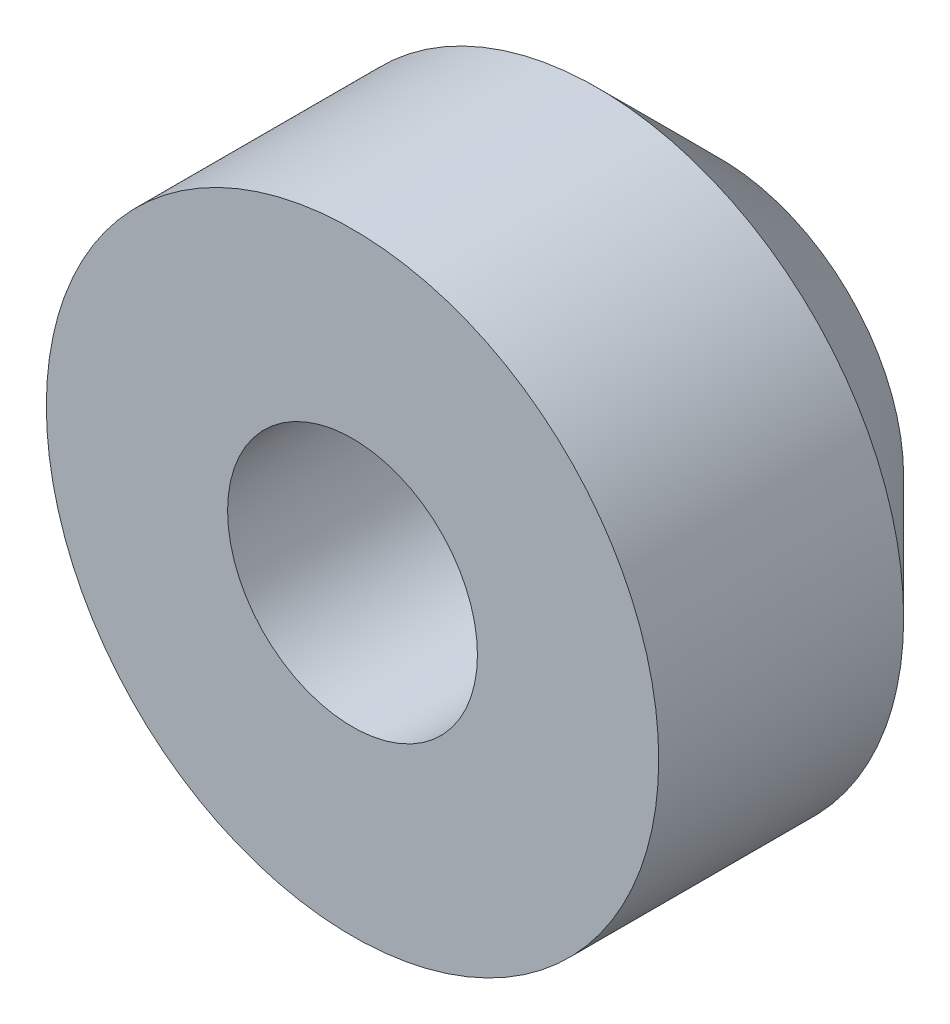
SolidWorks part; units mm, degrees
ref_plane "Front Plane" through (0, 0, 0) normal (0, 0, 1) x (1, 0, 0)
ref_plane "Top Plane" through (0, 0, 0) normal (0, 1, 0) x (1, 0, 0)
ref_plane "Right Plane" through (0, 0, 0) normal (1, 0, 0) x (0, 0, -1)
sketch "Sketch1" plane through (0, 0, 0) normal (0, 0, 1) x (1, 0, 0)
  circle A0 centre (0, 0) radius 5.1
  circle A1 centre (0, 0) radius 12.5
  dimension "D1" = 25
  dimension "D2" = 10.2
extrude "Boss-Extrude1" add sketch "Sketch1" along normal blind 15
chamfer "Chamfer1" distance 5 angle 45 1 edges at (12.5, 0, 0)
